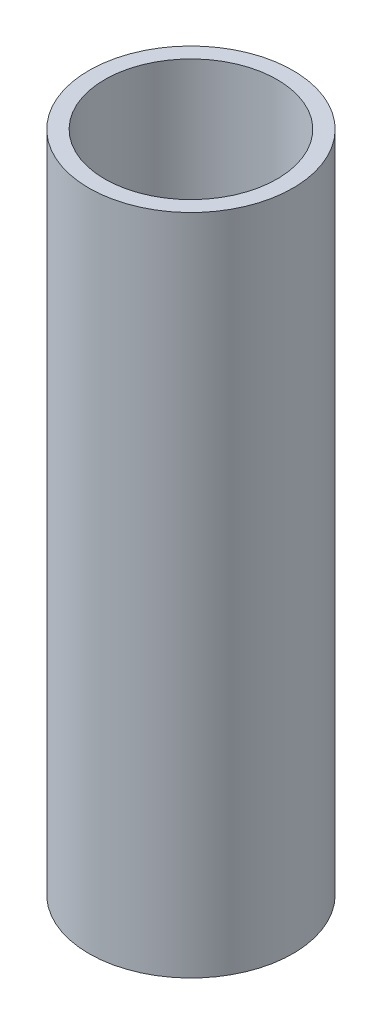
SolidWorks part; units mm, degrees
ref_plane "Спереди" through (0, 0, 0) normal (0, 0, 1) x (1, 0, 0)
ref_plane "Сверху" through (0, 0, 0) normal (0, 1, 0) x (1, 0, 0)
ref_plane "Справа" through (0, 0, 0) normal (1, 0, 0) x (0, 0, -1)
sketch "Эскиз1" plane through (0, 0, 0) normal (0, 1, 0) x (1, 0, 0)
  circle A0 centre (0, 0) radius 10
  circle A1 centre (0, 0) radius 8.45
  dimension "D1" = 20
  dimension "D2" = 16.9
extrude "Бобышка-Вытянуть1" add sketch "Эскиз1" along normal blind 65
